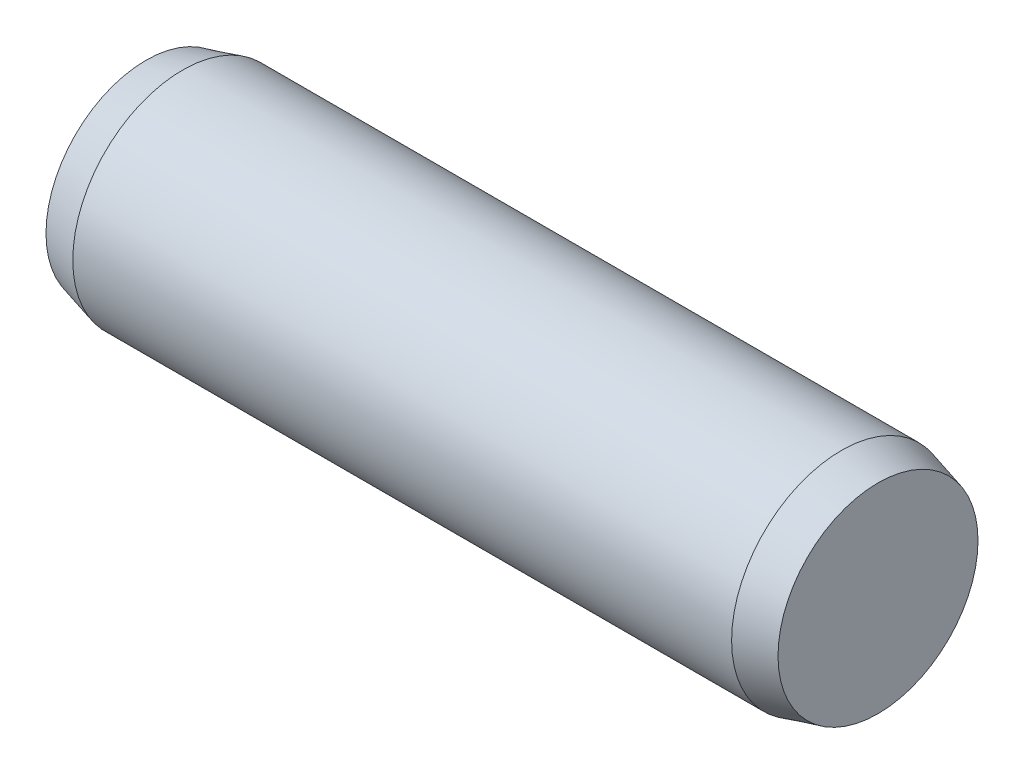
SolidWorks part; units mm, degrees
ref_plane "Front" through (0, 0, 0) normal (0, 0, 1) x (1, 0, 0)
ref_plane "Top" through (0, 0, 0) normal (0, 1, 0) x (1, 0, 0)
ref_plane "Right" through (0, 0, 0) normal (1, 0, 0) x (0, 0, -1)
sketch "Sketch1" plane through (0, 0, 0) normal (0, 0, 1) x (1, 0, 0)
  line L0 (0, 0) -> (10, 0)
  line L1 (10, 0) -> (10, 1.366)
  line L2 (10, 1.366) -> (9.5, 1.5)
  line L3 (9.5, 1.5) -> (0.5, 1.5)
  line L4 (0.5, 1.5) -> (0, 1.366)
  line L5 (0, 1.366) -> (0, 0)
  line L6 (-6.9767, 0) -> (2.6973, 0) construction
  dimension "l" = 10
  dimension "D2" = 15
  dimension "D3" = 15
  dimension "d" = 3
  dimension "c" = 0.5
  dimension "D6" = 0.5
revolve "Base-Revolve" add sketch "Sketch1" angle 360 about L6
equation "\"D6@Sketch1\" = \"c@Sketch1\""
